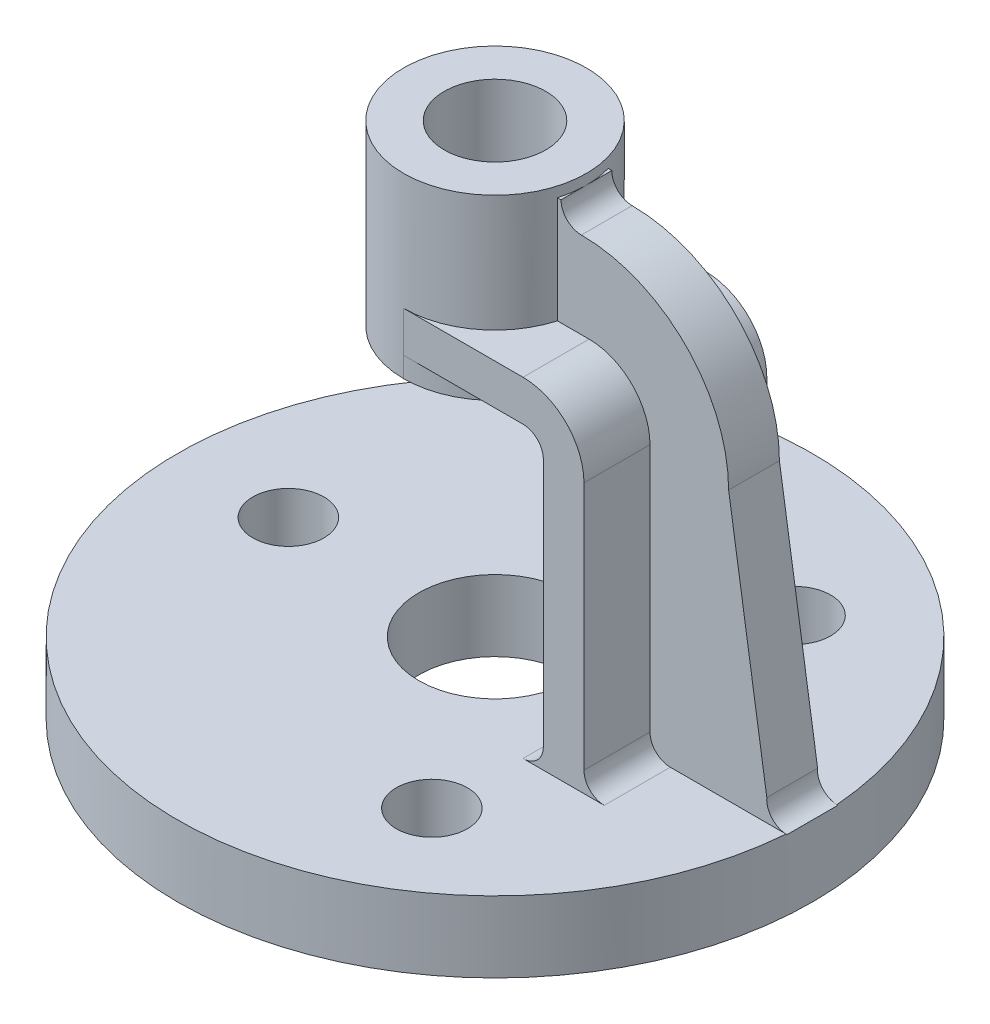
SolidWorks part; units mm, degrees
ref_plane "Alzado" through (0, 0, 0) normal (0, 0, 1) x (1, 0, 0)
ref_plane "Planta" through (0, 0, 0) normal (0, 1, 0) x (1, 0, 0)
ref_plane "Vista lateral" through (0, 0, 0) normal (1, 0, 0) x (0, 0, -1)
sketch "Croquis1" plane through (0, 0, 0) normal (0, 1, 0) x (1, 0, 0)
  line L0 (0, 27.5544) -> (0, -27.5544) construction
  line L1 (-46.7273, 0) -> (46.7273, 0) construction
  circle A0 centre (0, 0) radius 62.5
  circle A1 centre (0, 0) radius 15
  point P5 (0, 0)
  point P6 (0, 0)
  dimension "D1" = 125
  dimension "D2" = 30
extrude "Saliente-Extruir1" add sketch "Croquis1" along normal blind 14
sketch3d "Croquis3D1" plane through (0, 0, 0) normal (0, 0, 1) x (1, 0, 0)
  dimension "D1" = 67
sketch "Croquis4" plane through (0, 67, 0) normal (0, 1, 0) x (1, 0, 0)
  circle A0 centre (0, 0) radius 10
  circle A1 centre (0, 0) radius 18
  dimension "D1" = 20
  dimension "D2" = 36
extrude "Saliente-Extruir3" add sketch "Croquis4" along normal blind 35 separate body
sketch "Croquis5" plane through (0, 0, 0) normal (0, 0, 1) x (1, 0, 0)
  line L0 (0, -2.6292) -> (0, 106.9408) construction
  line L1 (-90.745, 67) -> (90.745, 67) construction
  line L2 (68.75, 67) -> (-68.75, 67) construction
  line L4 (18, 102) -> (18, 57.6081) construction
  line L5 (62.5, 14) -> (-62.5, 14) construction
  line L6 (15.7507, 96) -> (38.6801, 96) construction
  line L7 (22, 72.655) -> (22, 65.5534) construction
  line L8 (18, 67) -> (18, 102) construction
  line L9 (18, 102) -> (-18, 102) construction
  line L11 (23.5155, 79) -> (23.5155, 60.9613) construction
  line L12 (51, 67) -> (58.5155, 18.3513)
  line L13 (58.5155, 32.9434) -> (58.5155, -4.326) construction
  line L14 (27.5155, 32.9434) -> (27.5155, -4.326) construction
  line L15 (27.5155, 18) -> (27.5155, 67)
  line L17 (23.5155, 14) -> (62.5, 14)
  line L18 (0, 96) -> (0, 71)
  line L20 (22, 71) -> (23.5155, 71)
  line L26 (18, 67) -> (15.091, 67)
  line L27 (0, 100) -> (0, 71)
  line L28 (18, 100) -> (15.091, 100)
  line L29 (15.091, 100) -> (15.091, 67)
  arc A3 (22, 71) -> (18, 67) centre (22, 67) ccw
  arc A8 (18, 100) -> (22, 96) centre (22, 100) ccw
  arc A9 (51, 67) -> (22, 96) centre (22, 67) ccw
  arc A10 (58.5155, 18.3513) -> (62.5, 14) centre (62.5, 18) ccw
  arc A11 (23.5155, 14) -> (27.5155, 18) centre (23.5155, 18) ccw
  arc A14 (27.5155, 67) -> (23.5155, 71) centre (23.5155, 67) ccw
  point P7 (0, 67)
  dimension "D4" = 8
  dimension "D3" = 4
  dimension "D5" = 31
extrude "Saliente-Extruir4" add sketch "Croquis5" along normal mid plane 10
sketch "Croquis6" plane through (0, 0, 0) normal (0, 0, 1) x (1, 0, 0)
  line L0 (0, 106.9408) -> (0, 12.4452) construction
  line L1 (0, -2.6292) -> (0, 106.9408) construction
  line L2 (-70.3767, 67) -> (90.745, 67) construction
  line L3 (-90.745, 67) -> (90.745, 67) construction
  line L4 (23.5155, 79) -> (23.5155, 60.9613) construction
  line L5 (23.5155, 67) -> (60.7062, 93.1914) construction
  line L6 (23.5155, 71) -> (0, 71)
  line L7 (35.5155, 67) -> (35.5155, 18)
  line L8 (27.5155, 67) -> (27.5155, 18)
  line L9 (23.5155, 79) -> (0, 79)
  line L10 (23.5155, 14) -> (62.2997, 14) construction
  line L11 (39.5155, 14) -> (39.5155, 12.9109) construction
  line L12 (0, 79) -> (0, 71)
  line L13 (23.5155, 14) -> (39.5155, 14)
  arc A0 (23.5155, 71) -> (27.5155, 67) centre (23.5155, 67) cw
  arc A1 (27.5155, 67) -> (23.5155, 71) centre (23.5155, 67) ccw construction
  arc A2 (27.5155, 18) -> (23.5155, 14) centre (23.5155, 18) cw
  arc A3 (35.5155, 18) -> (39.5155, 14) centre (39.5155, 18) ccw
  arc A4 (23.5155, 79) -> (35.5155, 67) centre (23.5155, 67) cw
  arc A5 (35.5155, 18) -> (23.5155, 6) centre (23.5155, 18) cw construction
  dimension "D1" = 8
extrude "Saliente-Extruir5" add sketch "Croquis6" along normal mid plane 36
sketch "Croquis8" plane through (0, 0, 0) normal (0, 1, 0) x (1, 0, 0)
  line L0 (0, 10) -> (0, -10)
  arc A0 (0, -10) -> (0, 10) centre (0, 0) ccw
extrude "Cortar-Extruir2" cut sketch "Croquis8" along normal up to next
hole_wizard "Taladro1" positions "Croquis3D3" profile "Croquis10" legacy end condition up to next
sketch3d "Croquis3D3"
  line L0 (-62.5, 14, 0) -> (62.5, 14, 0) construction
  line L3 (0, 0, 0) -> (34.0104, 0.005, -43.5313) construction
  line L4 (0, 0, 0) -> (28.5637, 17.3615, 43.9815) construction
  line L5 (0, 0, 0) -> (0, 0, -61.4691) construction
  circle A0 centre (0, 0, 0) radius 43.0257 construction
  arc A1 (62.2997, 14, -5) -> (62.2997, 14, 5) centre (0, 14, 0) ccw construction
  point P0 (-40.6842, 14, 0)
  point P2 (25.9122, 14, -33.1657)
  point P4 (23.0332, 14, 35.4658)
  point P10 (14, 40.6842, 0)
  point P18 (0, 76.5, 0)
  point P33 (0, 0, 0)
  point P34 (0, 0, 0)
  point P35 (0, 0, 0)
  point P36 (0, 0, 0)
  point P37 (23.667, 14, 35.0959)
  point P38 (23.0292, 14, 35.4579)
  point P39 (0, 0, 0)
  point P40 (23.0332, 14, 35.4658)
  point P41 (0, 0, 0)
  point P42 (0, 0, 0)
  dimension "D1" = 108
  dimension "D2" = 38
sketch "Croquis10" plane through (-40.6842, 14, 0) normal (1, 0, 0) x (0, 0, 1)
  line L0 (0, 0) -> (0, 14)
  line L1 (0, 14) -> (7, 14)
  line L2 (7, 14) -> (7, 0)
  line L3 (7, 0) -> (0, 0)
  line L4 (0, 110) -> (0, -10) construction
  dimension "Diámetro" = 14
  dimension "Profundidad" = 14
